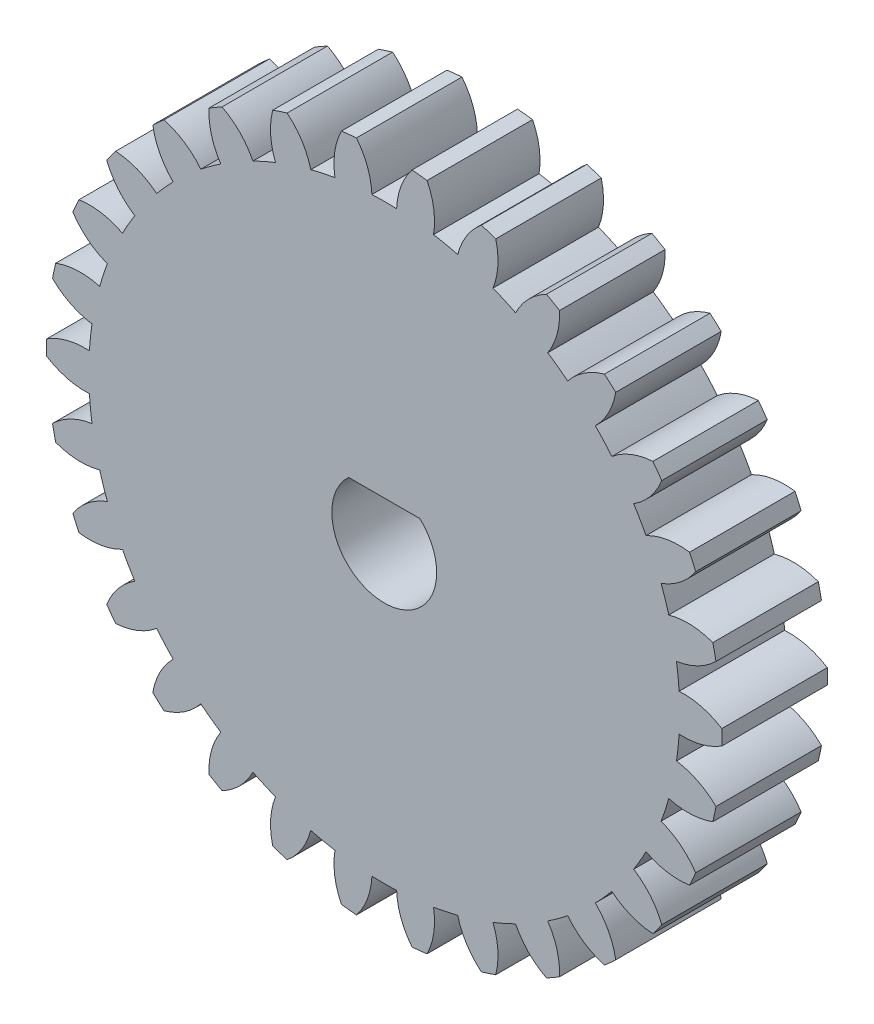
SolidWorks part; units mm, degrees
material "ABS"
ref_plane "Front Plane" through (0, 0, 0) normal (0, 0, 1) x (1, 0, 0)
ref_plane "Top Plane" through (0, 0, 0) normal (0, 1, 0) x (1, 0, 0)
ref_plane "Right Plane" through (0, 0, 0) normal (1, 0, 0) x (0, 0, -1)
sketch "Sketch1" plane through (0, 0, 0) normal (0, 0, 1) x (1, 0, 0)
  circle A0 centre (0, 0) radius 20.32
  dimension "D1" = 40.64
extrude "Outer Circle" add sketch "Sketch1" along normal blind 6.35
sketch "Sketch2" plane through (0, 0, 6.35) normal (0, 0, 1) x (1, 0, 0)
  line L0 (0.9984, 19.05) -> (-0.9984, 19.05) construction
  line L1 (2.9842, 18.8413) -> (0.9984, 19.05) construction
  line L2 (0, 19.05) -> (0, 0) construction
  line L3 (0, 0) -> (1.9913, 18.9456) construction
  line L4 (-1.442, 20.2688) -> (0, 16.307) construction
  line L5 (0, 16.307) -> (1.442, 20.2688) construction
  line L6 (-0.7438, 17.7644) -> (0, 0) construction
  circle A0 centre (0, 0) radius 17.78 construction
  circle A1 centre (0, 0) radius 19.05 construction
  arc A2 (-0.7438, 17.7644) -> (0.7438, 17.7644) centre (0, 0) cw
  arc A3 (-1.671, 20.2512) -> (1.671, 20.2512) centre (0, 0) cw
  circle A4 centre (0, 0) radius 20.32 construction
  arc A5 (-1.671, 20.2512) -> (-0.7438, 17.7644) centre (-5.0227, 17.5853) cw
  arc A6 (0.7438, 17.7644) -> (1.671, 20.2512) centre (5.0227, 17.5853) cw
  point P7 (0, 19.05)
  point P10 (1.9913, 18.9456)
  point P17 (0, 17.78)
  point P19 (0, 20.32)
  dimension "D1" = 35.56
  dimension "D2" = 38.1
  dimension "D3" = 6
  dimension "D4" = 20
extrude "Tooth Cut" cut sketch "Sketch2" against normal through all
pattern_circular "Teeth Pattern" count 30 over 360 about axis through (0, 0, 0) along (0, 0, 1) of "Tooth Cut"
ref_plane "Plane1" through (0, 0, 3.175) normal (0, 0, 1) x (1, 0, 0)
sketch "Pitch Diameter" plane through (0, 0, 3.175) normal (0, 0, 1) x (1, 0, 0)
  circle A0 centre (0, 0) radius 19.05 construction
  circle A1 centre (0, 0) radius 19.05
sketch "Sketch3" plane through (0, 0, 6.35) normal (0, 0, 1) x (1, 0, 0)
  line L0 (-2.142, 2.3177) -> (2.142, 2.3177)
  line L1 (0, -3.1559) -> (0, 2.3177) construction
  circle A0 centre (0, 0) radius 3.156
  dimension "D1" = 6.3119
  dimension "D2" = 5.4737
extrude "Cut-Extrude1" cut sketch "Sketch3" against normal through all contours A0 L1 L0 | L1 A0 L0
equation "\"No. of Teeth\"= 30"
equation "\"Module\"= 1 / 20'Inverse of Pitch"
equation "\"D1@Sketch1\"=(\"No. of Teeth\"+2)*\"Module\""
equation "\"D1@Sketch2\"=(\"No. of Teeth\"-2)*\"Module\""
equation "\"D2@Sketch2\"= \"No. of Teeth\" * \"Module\"'Pitch Diameter"
equation "\"D3@Sketch2\"=180/\"No. of Teeth\""
equation "\"D1@Teeth Pattern\" = \"No. of Teeth\""
